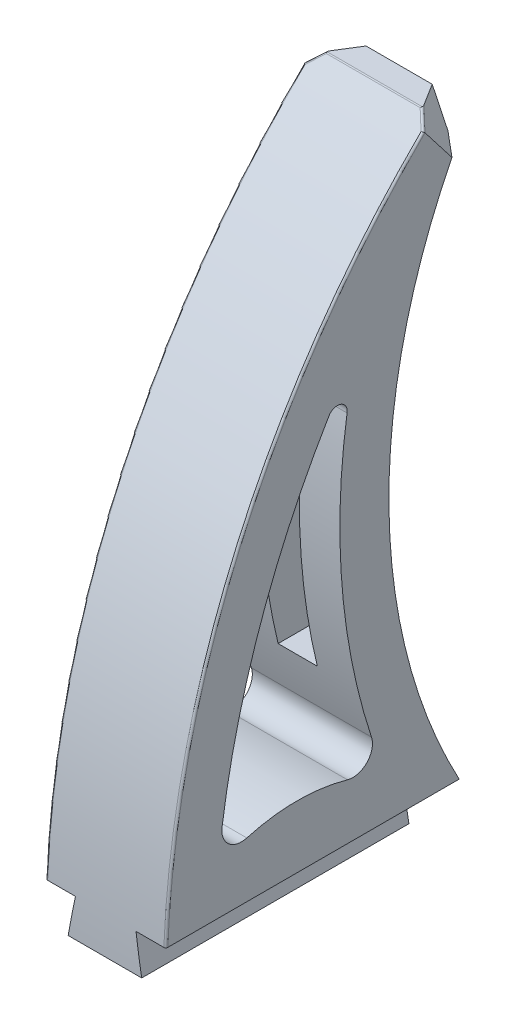
SolidWorks part; units mm, degrees
ref_plane "Front Plane" through (0, 0, 0) normal (0, 0, 1) x (1, 0, 0)
ref_plane "Top Plane" through (0, 0, 0) normal (0, 1, 0) x (1, 0, 0)
ref_plane "Right Plane" through (0, 0, 0) normal (1, 0, 0) x (0, 0, -1)
sketch "Sketch1" plane through (0, 0, 0) normal (0, 0, 1) x (1, 0, 0)
  line L0 (0, 0) -> (0, -27.8746) construction
  line L1 (-15.5575, 76.2) -> (15.5575, 76.2)
  line L2 (-15.5575, 76.2) -> (-15.5575, -76.2)
  line L3 (-15.5575, -76.2) -> (-7.8455, -76.2)
  line L4 (15.5575, 76.2) -> (15.5575, -76.2)
  line L5 (-15.5575, 76.2) -> (15.5575, -76.2) construction
  line L6 (-15.5575, -76.2) -> (15.5575, 76.2) construction
  line L7 (7.8455, -76.2) -> (9.525, -85.725)
  line L8 (-7.8455, -76.2) -> (-9.525, -85.725)
  line L9 (-9.525, -85.725) -> (9.525, -85.725)
  line L10 (7.8455, -76.2) -> (15.5575, -76.2)
  point P0 (0, 0)
  point P12 (0, -85.725)
  dimension "D1" = 31.115
  dimension "D2" = 152.4
  dimension "D3" = 20
  dimension "D4" = 19.05
  dimension "D5" = 9.525
extrude "Boss-Extrude1" add sketch "Sketch1" along normal blind 76.2
sketch "Sketch2" plane through (15.5575, 0, 0) normal (1, 0, 0) x (0, 0, -1)
  line L0 (-76.2, -76.2) -> (0, -76.2) construction
  line L1 (0, -85.725) -> (-6.985, -85.725)
  line L2 (0, -85.725) -> (0, -76.2)
  line L3 (0, -76.2) -> (-6.985, -76.2)
  line L4 (-6.985, -85.725) -> (-6.985, -76.2)
  dimension "D1" = 6.985
extrude "Cut-Extrude1" cut sketch "Sketch2" against normal through all
sketch "Sketch3" plane through (15.5575, 0, 0) normal (1, 0, 0) x (0, 0, -1)
  line L14 (-76.2, 76.2) -> (0, 76.2) construction
  line L15 (-76.2, -76.2) -> (-76.2, 76.2) construction
  line L16 (-76.2, -85.725) -> (-76.2, -76.2) construction
  line L17 (0, -76.2) -> (0, 76.2) construction
  line L18 (-76.2, -85.725) -> (-76.2, -76.2)
  line L19 (-76.2, -76.2) -> (-76.2, 76.2)
  line L20 (-76.2, 76.2) -> (-6.5418, 76.2)
  line L21 (0, -76.2) -> (0, 67.7594)
  arc A4 (-6.5418, 76.2) -> (-76.2, -85.725) centre (146.8317, -85.725) ccw
  arc A5 (0, 67.7594) -> (0, -76.2) centre (133.1876, -4.2203) ccw
extrude "Cut-Extrude2" cut sketch "Sketch3" against normal through all
sketch "Sketch6" plane through (15.5575, 0, 0) normal (1, 0, 0) x (0, 0, -1)
  line L6 (-62.3225, -63.5) -> (-19.8242, -63.5)
  arc A2 (-28.9344, -61.8834) -> (-22.7163, -55.413) centre (-27.5427, -56.9978) ccw
  arc A3 (-55.008, -61.8834) -> (-61.4297, -56.2868) centre (-56.3997, -56.9978) cw
  arc A6 (-26.5466, 33.3523) -> (-19.8242, -63.5) centre (133.1876, -4.2203) ccw
  arc A7 (-26.5466, 33.3523) -> (-62.3225, -63.5) centre (146.8317, -85.725) ccw
  arc A11 (-26.5466, 33.3523) -> (-22.7163, -55.413) centre (133.1876, -4.2203) ccw
  arc A12 (-26.5466, 33.3523) -> (-61.4297, -56.2868) centre (146.8317, -85.725) ccw
  arc A13 (-55.008, -61.8834) -> (-28.9344, -61.8834) centre (-41.9712, -107.6502) cw
  dimension "D2" = 5.08
  dimension "D1" = 12.7
extrude "Cut-Extrude3" cut sketch "Sketch6" against normal through all
fillet "Fillet1" radius 2.54 1 edges at (0, 33.3523, 26.5466)
sketch "Sketch7" plane through (0, 0, 0) normal (1, 0, 0) x (0, 0, -1)
  line L0 (-30.6991, 4.0162) -> (-17.9818, 4.0162)
  line L2 (-26.2642, -42.9738) -> (-13.1619, -42.9738)
  arc A0 (-29.0387, 20.4641) -> (-22.7163, -55.413) centre (133.1876, -4.2203) ccw construction
  arc A1 (0, 67.7594) -> (0, -76.2) centre (133.1876, -4.2203) ccw construction
  arc A2 (-30.6991, 4.0162) -> (-26.2642, -42.9738) centre (133.1876, -4.2203) ccw
  arc A3 (-17.9818, 4.0162) -> (-13.1619, -42.9738) centre (133.1876, -4.2203) ccw
  dimension "D1" = 46.99
extrude "Cut-Extrude4" cut sketch "Sketch7" against normal mid plane 10.16
sketch "Sketch9" plane through (15.5575, 0, 0) normal (1, 0, 0) x (0, 0, -1)
  line L0 (-6.5418, 76.2) -> (0, 67.7594)
ref_plane "Plane2" through (15.5575, 76.2, 6.5418) normal (0, -0.7904, -0.6126) x (-1, 0, 0)
sketch "Sketch10" plane through (15.5575, 76.2, 6.5418) normal (0, -0.7904, -0.6126) x (-1, 0, 0)
  line L4 (15.5575, 5.1706) -> (15.5575, 19.0294) construction
  line L5 (0, 5.1706) -> (31.115, 5.1706) construction
  line L6 (0, 5.1706) -> (6.985, 5.1706)
  line L7 (6.985, 5.1706) -> (0, -3.6559)
  line L8 (0, 0) -> (0, -88.1882) construction
  line L9 (0, 5.1706) -> (0, -3.6559)
  line L10 (31.115, 5.1706) -> (31.115, -3.6559)
  line L11 (24.13, 5.1706) -> (31.115, -3.6559)
  line L12 (31.115, 5.1706) -> (24.13, 5.1706)
  dimension "D1" = 8.8265
  dimension "D2" = 6.985
extrude "Cut-Extrude6" cut sketch "Sketch10" against normal mid plane 30.226
fillet "Fillet2" radius 0.508 5 edges at (-15.5575, 5.0909, 56.873) (-14.1116, 74.9302, 7.8714) (0, 76.2, 6.5418) (15.5575, 5.0909, 56.873) (14.1116, 74.9302, 7.8714)
